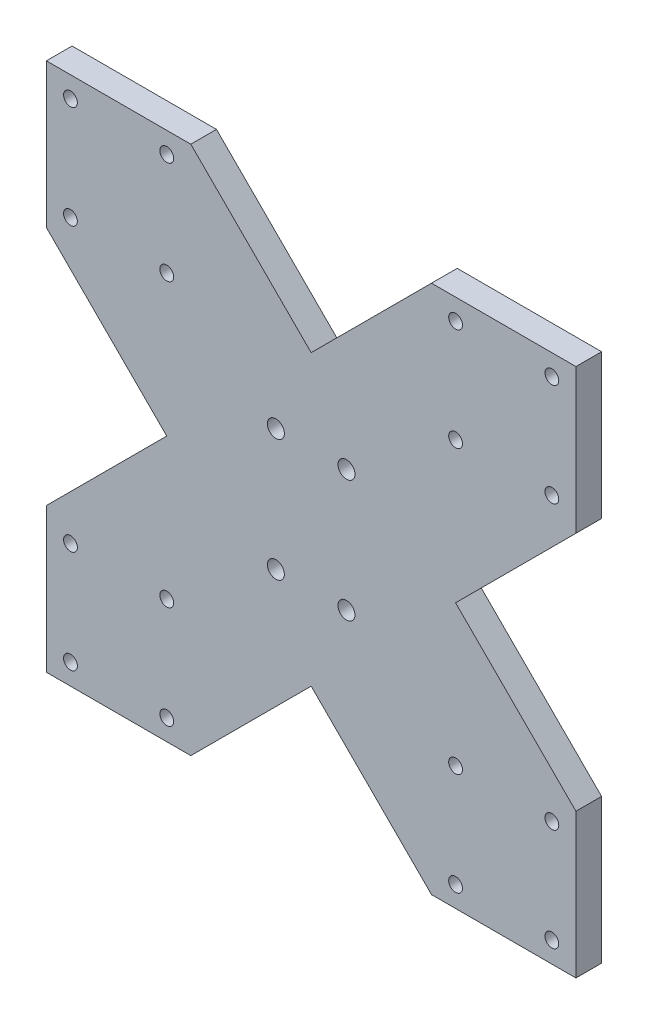
SolidWorks part; units mm, degrees
ref_plane "Front Plane" through (0, 0, 0) normal (0, 0, 1) x (1, 0, 0)
ref_plane "Top Plane" through (0, 0, 0) normal (0, 1, 0) x (1, 0, 0)
ref_plane "Right Plane" through (0, 0, 0) normal (1, 0, 0) x (0, 0, -1)
sketch "Sketch1" plane through (0, 0, 0) normal (0, 0, 1) x (1, 0, 0)
  line L0 (-82.5, 37.5) -> (-45, 0)
  line L1 (-82.5, 82.5) -> (-37.5, 82.5)
  line L2 (-82.5, 82.5) -> (-82.5, 37.5)
  line L3 (0, 48.5911) -> (0, -38.739) construction
  line L4 (-69.3884, 0) -> (64.4048, 0) construction
  line L5 (55, 0) -> (-55, 0) construction
  line L6 (-37.5, 82.5) -> (0, 45)
  line L7 (0, -55) -> (0, 55) construction
  line L8 (37.5, 82.5) -> (0, 45)
  line L9 (82.5, 82.5) -> (82.5, 37.5)
  line L10 (82.5, 82.5) -> (37.5, 82.5)
  line L11 (82.5, 37.5) -> (45, 0)
  line L12 (82.5, -37.5) -> (45, 0)
  line L13 (82.5, -82.5) -> (37.5, -82.5)
  line L14 (82.5, -82.5) -> (82.5, -37.5)
  line L15 (37.5, -82.5) -> (0, -45)
  line L16 (-37.5, -82.5) -> (0, -45)
  line L17 (-82.5, -82.5) -> (-82.5, -37.5)
  line L18 (-82.5, -82.5) -> (-37.5, -82.5)
  line L19 (-82.5, -37.5) -> (-45, 0)
  dimension "D1" = 82.5
  dimension "D2" = 82.5
  dimension "D3" = 45
  dimension "D4" = 45
  dimension "D5" = 45
  dimension "D6" = 45
extrude "Boss-Extrude1" add sketch "Sketch1" along normal blind 8
hole_wizard "M4 Clearance Hole1" positions "Sketch3" profile "Sketch2" hole size "M4" standard "ISO" end condition through all
sketch "Sketch3" plane through (0, 0, 8) normal (0, 0, 1) x (1, 0, 0)
  line L5 (-82.5, 82.5) -> (-82.5, 37.5) construction
  line L6 (-37.5, 82.5) -> (-82.5, 82.5) construction
  point P0 (-75, 76)
  point P2 (-45, 76)
  point P4 (-45, 44)
  point P6 (-75, 44)
  point P34 (-75, -44)
  point P35 (-45, -44)
  point P36 (-45, -76)
  point P37 (-75, -76)
  point P38 (75, -76)
  point P39 (45, -76)
  point P40 (45, -44)
  point P41 (75, -44)
  point P44 (75, 44)
  point P45 (45, 44)
  point P46 (45, 76)
  point P47 (75, 76)
  dimension "D2" = 30
  dimension "D3" = 32
  dimension "D4" = 30
  dimension "D5" = 7.5
  dimension "D6" = 32
  dimension "D7" = 7.5
  dimension "D8" = 6.5
  dimension "D11" = 6.5
sketch "Sketch2" plane through (-75, 76, 8) normal (1, 0, 0) x (0, -1, 0)
  line L0 (0, 0) -> (0, 8)
  line L1 (0, 8) -> (2.15, 8)
  line L2 (2.15, 8) -> (2.15, 0)
  line L5 (2.15, 0) -> (0, 0)
  line L11 (0, -6.35) -> (0, 107.95) construction
  dimension "Thru Hole Dia." = 4.3
  dimension "Thru Hole Depth" = 8
hole_wizard "M5 Clearance Hole1" positions "Sketch5" profile "Sketch4" hole size "M5" standard "ISO" end condition through all
sketch "Sketch5" plane through (0, 0, 8) normal (0, 0, 1) x (1, 0, 0)
  line L0 (0, -55) -> (0, 55) construction
  line L1 (55, 0) -> (-55, 0) construction
  line L2 (-73.4531, 0) -> (68.3865, 0) construction
  line L4 (0, 47.7355) -> (0, -28.9141) construction
  point P0 (-11, 19)
  point P22 (-11, -19)
  point P23 (11, -19)
  point P24 (11, 19)
  dimension "D1" = 11
  dimension "D2" = 19
sketch "Sketch4" plane through (-11, 19, 8) normal (1, 0, 0) x (0, -1, 0)
  line L0 (0, 0) -> (0, 8)
  line L1 (0, 8) -> (2.65, 8)
  line L2 (2.65, 8) -> (2.65, 0)
  line L5 (2.65, 0) -> (0, 0)
  line L11 (0, -6.35) -> (0, 107.95) construction
  dimension "Thru Hole Dia." = 5.3
  dimension "Thru Hole Depth" = 8
